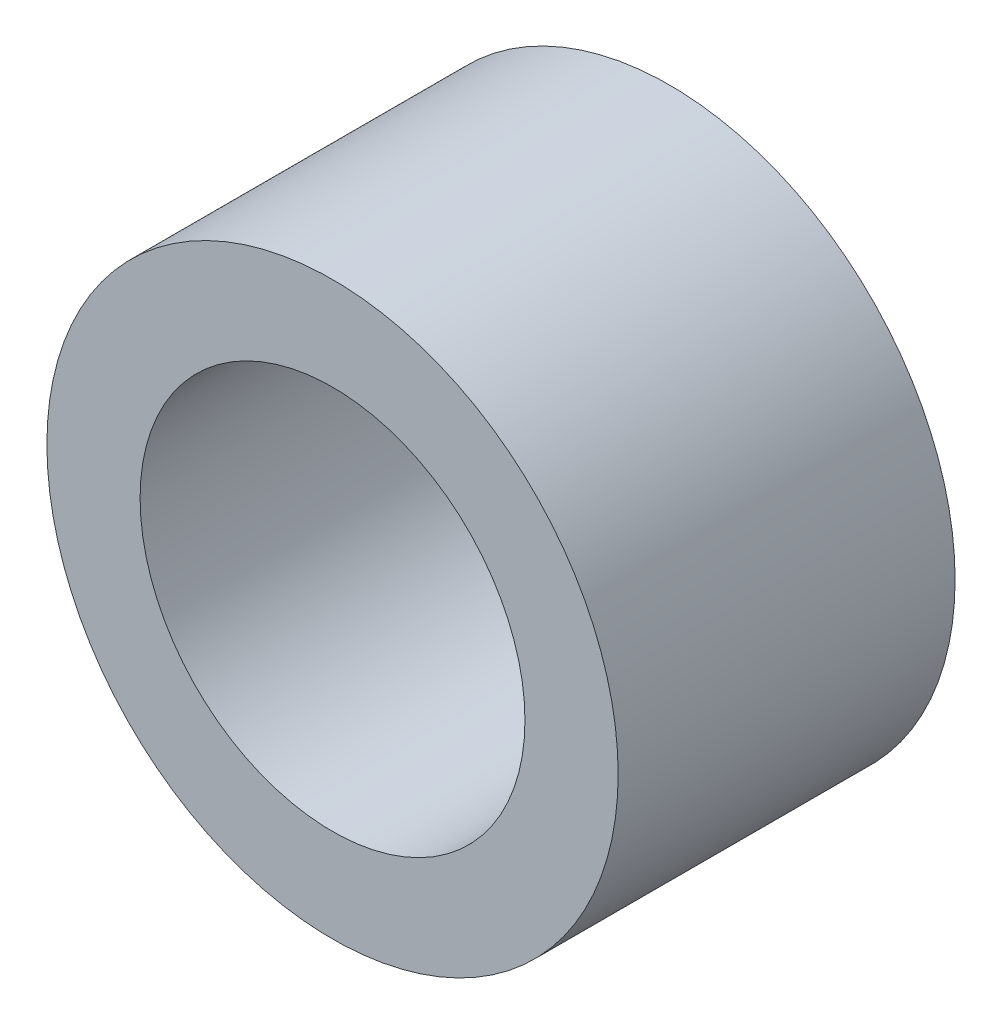
SolidWorks part; units mm, degrees
ref_plane "Front Plane" through (0, 0, 0) normal (0, 0, 1) x (1, 0, 0)
ref_plane "Top Plane" through (0, 0, 0) normal (0, 1, 0) x (1, 0, 0)
ref_plane "Right Plane" through (0, 0, 0) normal (1, 0, 0) x (0, 0, -1)
sketch "Sketch3" plane through (0, 0, 0) normal (0, 0, 1) x (1, 0, 0)
  circle A0 centre (0, 0) radius 5.9
  circle A1 centre (0, 0) radius 3.975
  dimension "D1" = 11.8
  dimension "D2" = 7.95
extrude "Boss-Extrude1" add sketch "Sketch3" along normal blind 6.96
